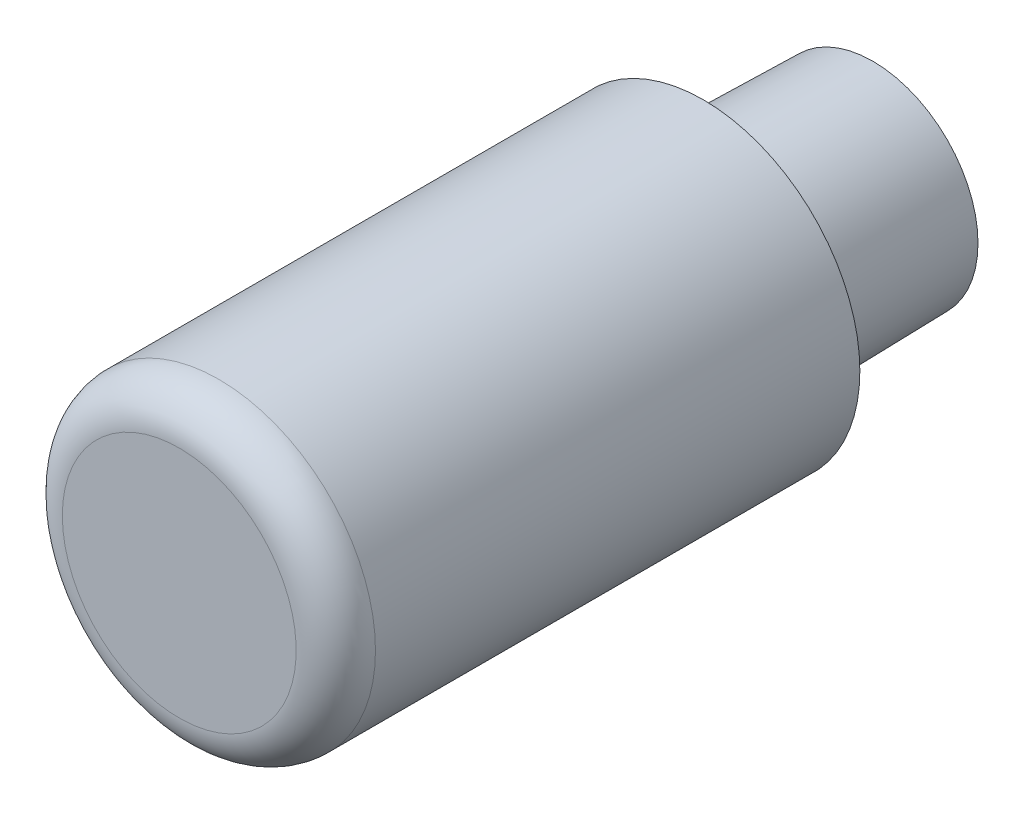
SolidWorks part; units mm, degrees
material "Brass"
ref_plane "Front Plane" through (0, 0, 0) normal (0, 0, 1) x (1, 0, 0)
ref_plane "Top Plane" through (0, 0, 0) normal (0, 1, 0) x (1, 0, 0)
ref_plane "Right Plane" through (0, 0, 0) normal (1, 0, 0) x (0, 0, -1)
sketch "Sketch1" plane through (0, 0, 0) normal (1, 0, 0) x (0, 0, -1)
  line L0 (-26.803, 0) -> (34.189, 0) construction
  line L1 (-38.6588, 0) -> (-38.6588, 10.033)
  line L2 (-38.6588, 10.033) -> (-5.08, 10.033)
  line L3 (-5.08, 10.033) -> (-5.08, 6.9596)
  line L4 (-5.08, 6.9596) -> (5.7912, 6.7319)
  line L5 (5.7912, 6.7319) -> (5.7912, 0)
  line L6 (-38.6588, 0) -> (5.7912, 0)
  dimension "D1" = 44.45
  dimension "D2" = 20.066
  dimension "D3" = 1.2
  dimension "D4" = 5.7912
  dimension "D5" = 13.9192
  dimension "D6" = 5.08
revolve "Revolve1" add sketch "Sketch1" angle 360 about L0
fillet "Fillet1" radius 2.54 1 edges at (10.033, 0, 38.6588)
